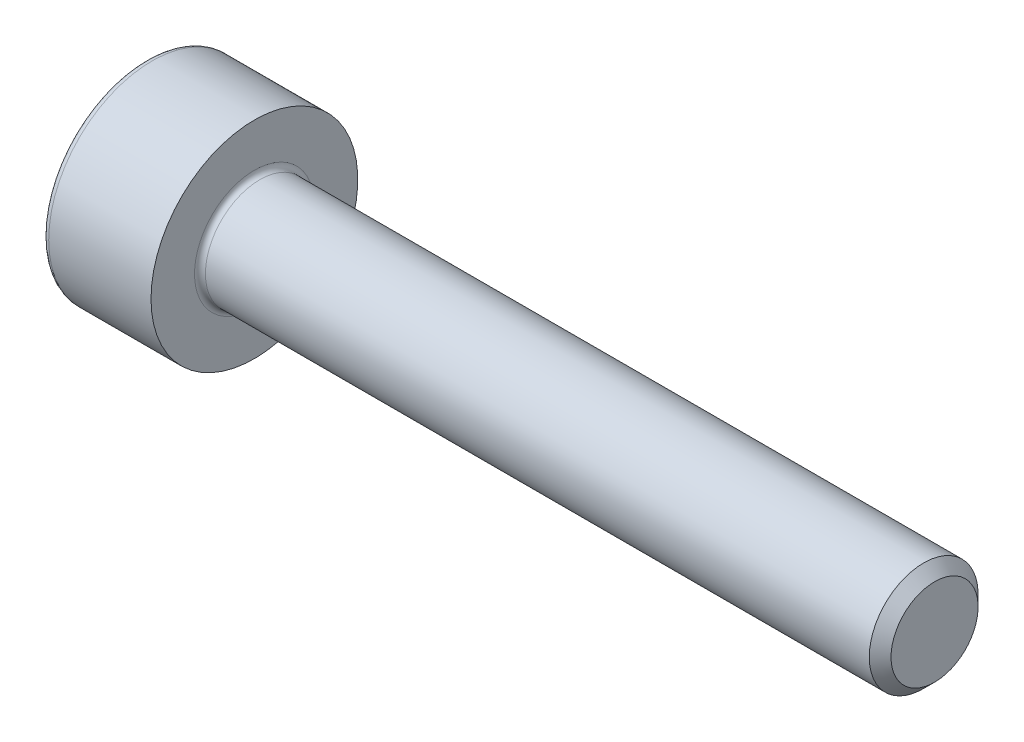
SolidWorks part; units mm, degrees
ref_plane "Front Plane" through (0, 0, 0) normal (0, 0, 1) x (1, 0, 0)
ref_plane "Top Plane" through (0, 0, 0) normal (0, 1, 0) x (1, 0, 0)
ref_plane "Right Plane" through (0, 0, 0) normal (1, 0, 0) x (0, 0, -1)
sketch "Sketch1" plane through (0, 0, 0) normal (0, 0, 1) x (1, 0, 0)
  line L0 (0, 0) -> (0, 1.9)
  line L1 (0, 1.9) -> (2, 1.9)
  line L2 (2, 1.9) -> (2, 0)
  line L3 (0, 0) -> (4.2799, 0) construction
  line L4 (2, 0) -> (14.5, 0)
  line L5 (14.5, 0) -> (14.5, 1)
  line L6 (14.5, 1) -> (2, 1)
  dimension "D1" = 12.5
revolve "Revolve1" add sketch "Sketch1" angle 360 about L3
fillet "Fillet1" radius 0.1 1 edges at (2, 0, 1)
fillet "Fillet2" radius 0.12 1 edges at (0, 0, 1.9)
chamfer "Chamfer1" distance 0.2 angle 45 1 edges at (14.5, 0, 1)
sketch "Sketch2" plane through (0, 0, 0) normal (-1, 0, 0) x (0, 0, 1)
  line L1 (0, 0.866) -> (-0.75, 0.433)
  line L2 (-0.75, 0.433) -> (-0.75, -0.433)
  line L3 (-0.75, -0.433) -> (0, -0.866)
  line L4 (0, -0.866) -> (0.75, -0.433)
  line L5 (0.75, -0.433) -> (0.75, 0.433)
  line L6 (0.75, 0.433) -> (0, 0.866)
  circle A0 centre (0, 0) radius 0.75 construction
extrude "Extrude1" cut sketch "Sketch2" against normal blind 1
